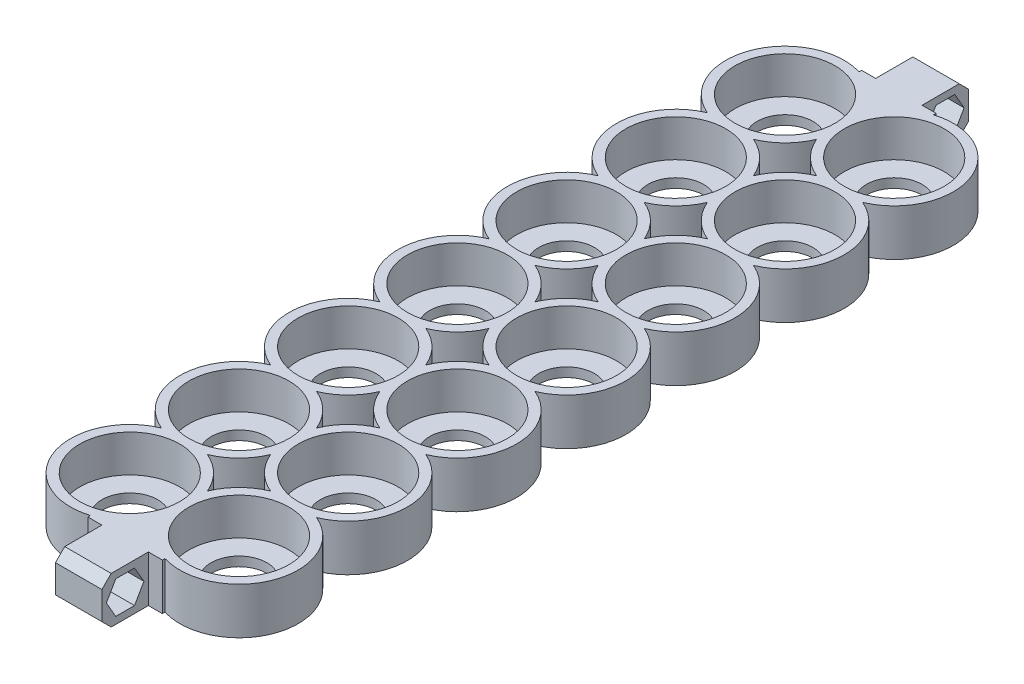
SolidWorks part; units mm, degrees
ref_plane "Front Plane" through (0, 0, 0) normal (0, 0, 1) x (1, 0, 0)
ref_plane "Top Plane" through (0, 0, 0) normal (0, 1, 0) x (1, 0, 0)
ref_plane "Right Plane" through (0, 0, 0) normal (1, 0, 0) x (0, 0, -1)
sketch "Sketch1" plane through (0, 0, 0) normal (1, 0, 0) x (0, 0, -1)
  line L0 (0, 27.0772) -> (0, -22.0037) construction
  line L1 (-12.75, 5) -> (-12.75, -5)
  line L2 (-12.75, -5) -> (-6, -5)
  line L3 (-6, -5) -> (-6, -3)
  line L4 (-6, -3) -> (-10.75, -3)
  line L5 (-10.75, -3) -> (-10.75, 5)
  line L6 (-10.75, 5) -> (-12.75, 5)
  point P5 (-12.75, 0)
  dimension "D1" = 10
  dimension "D2" = 2
  dimension "D3" = 21.5
  dimension "D4" = 12
  dimension "D5" = 2
revolve "Revolve1" add sketch "Sketch1" angle 360 about L0
sketch "Sketch2" plane through (0, -5, 0) normal (0, -1, 0) x (1, 0, 0)
  line L0 (0, 12.1827) -> (0, -11.4982) construction
pattern_linear "LPattern1" count 7 spacing 23.5 along (0, 0, -1) of "Revolve1"
sketch "Sketch3" plane through (0, -5, 0) normal (0, -1, 0) x (1, 0, 0)
  line L0 (-17.2986, 0) -> (17.8169, 0) construction
pattern_linear "LPattern2" count 2 spacing 23.5 along (1, 0, 0) of "Revolve1", "LPattern1"
ref_plane "Plane1" through (0, 0, 12.75) normal (0, 0, 1) x (1, 0, 0)
sketch "Sketch4" plane through (0, 0, 12.75) normal (0, 0, 1) x (1, 0, 0)
  line L0 (11.75, 5) -> (11.75, -5) construction
  line L1 (11.75, 5) -> (-12.75, 5) construction
  line L2 (19.7686, -5) -> (3.7314, -5)
  line L3 (19.7686, -5) -> (19.7686, 5)
  line L4 (19.7686, 5) -> (3.7314, 5)
  line L5 (3.7314, -5) -> (3.7314, 5)
  line L6 (19.7686, -5) -> (3.7314, 5) construction
  line L7 (19.7686, 5) -> (3.7314, -5) construction
  point P4 (11.75, 0)
extrude "Boss-Extrude1" add sketch "Sketch4" against normal up to next
sketch "Sketch5" plane through (0, 0, 12.75) normal (0, 0, 1) x (1, 0, 0)
  line L0 (11.75, 5) -> (11.75, -5) construction
  line L1 (19.7686, 5) -> (3.7314, 5) construction
  line L2 (3.7314, -5) -> (19.7686, -5) construction
  line L8 (16.75, -5) -> (6.75, -5)
  line L9 (16.75, -5) -> (16.75, 5)
  line L10 (16.75, 5) -> (6.75, 5)
  line L11 (6.75, -5) -> (6.75, 5)
  line L12 (16.75, -5) -> (6.75, 5) construction
  line L13 (16.75, 5) -> (6.75, -5) construction
  point P6 (11.75, 0)
  point P7 (11.75, 0)
  dimension "D1" = 10
  dimension "D2" = 10
extrude "Boss-Extrude2" add sketch "Sketch5" along normal blind 10
sketch "Sketch8" plane through (6.75, 0, 0) normal (-1, 0, 0) x (0, 0, 1)
  line L0 (12.75, 0) -> (22.75, 0) construction
  line L1 (12.75, -3.3) -> (12.75, 3.3) construction
  line L2 (22.75, 5) -> (22.75, -5) construction
  line L3 (17.75, 5) -> (17.75, -5) construction
  line L4 (22.75, 5) -> (12.75, 5) construction
  line L5 (22.75, -5) -> (12.75, -5) construction
  line L7 (19.7707, -3.5) -> (21.7915, 0)
  line L8 (21.7915, 0) -> (19.7707, 3.5)
  line L9 (19.7707, 3.5) -> (15.7293, 3.5)
  line L10 (15.7293, 3.5) -> (13.7085, 0)
  line L11 (13.7085, 0) -> (15.7293, -3.5)
  line L12 (15.7293, -3.5) -> (19.7707, -3.5)
  circle A0 centre (17.75, 0) radius 3.5 construction
  point P13 (0, 0)
  dimension "D1" = 7
extrude "Cut-Extrude1" cut sketch "Sketch8" against normal up to surface (10 mm away) up to face at (16.75, 0, 17.75)
chamfer "Chamfer3" distance 2 angle 45 2 edges at (11.75, -5, 22.75) (11.75, 5, 22.75)
ref_plane "Plane2" through (12.75, 0, 0) normal (1, 0, 0) x (0, 0, -1)
ref_plane "Plane3" through (0, 0, -64.5) normal (0, 0, -1) x (-1, 0, 0)
ref_plane "Plane4" through (0, 0, -76.5) normal (0, 0, 1) x (1, 0, 0)
ref_plane "Plane5" through (0, 0, -70.5) normal (0, 0, 1) x (1, 0, 0)
mirror "Mirror2" about plane through (0, 0, -70.5) normal (0, 0, 1) of "Boss-Extrude1", "Chamfer3", "Cut-Extrude1", "Boss-Extrude2"
